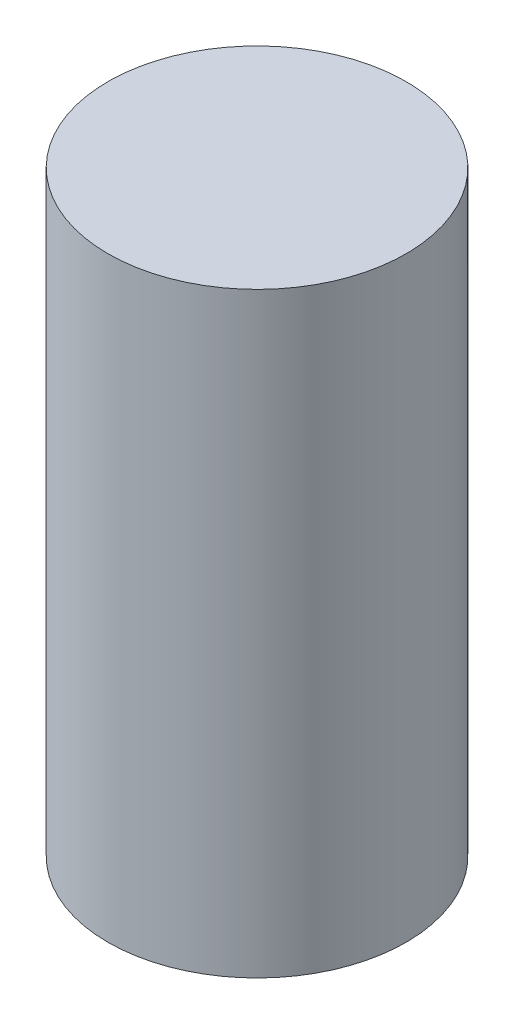
SolidWorks part; units mm, degrees
ref_plane "前视基准面" through (0, 0, 0) normal (0, 0, 1) x (1, 0, 0)
ref_plane "上视基准面" through (0, 0, 0) normal (0, 1, 0) x (1, 0, 0)
ref_plane "右视基准面" through (0, 0, 0) normal (1, 0, 0) x (0, 0, -1)
sketch "草图1" plane through (0, 0, 0) normal (0, 1, 0) x (1, 0, 0)
  circle A0 centre (0, 0) radius 10
  dimension "D1" = 20
extrude "凸台-拉伸1" add sketch "草图1" along normal blind 40
sketch "草图2" plane through (0, 0, 0) normal (0, 0, 1) x (1, 0, 0)
  line L0 (10, 40) -> (-10, 40) construction
  line L1 (-10, 40) -> (-10, 0) construction
  line L2 (-10, 0) -> (10, 0) construction
  circle A0 centre (0, 30) radius 2.5
  circle A1 centre (0, 10) radius 2.5
  dimension "D1" = 10
  dimension "D3" = 10
  dimension "D2" = 10
  dimension "D4" = 10
extrude "切除-拉伸1" cut sketch "草图2" against normal blind 40
